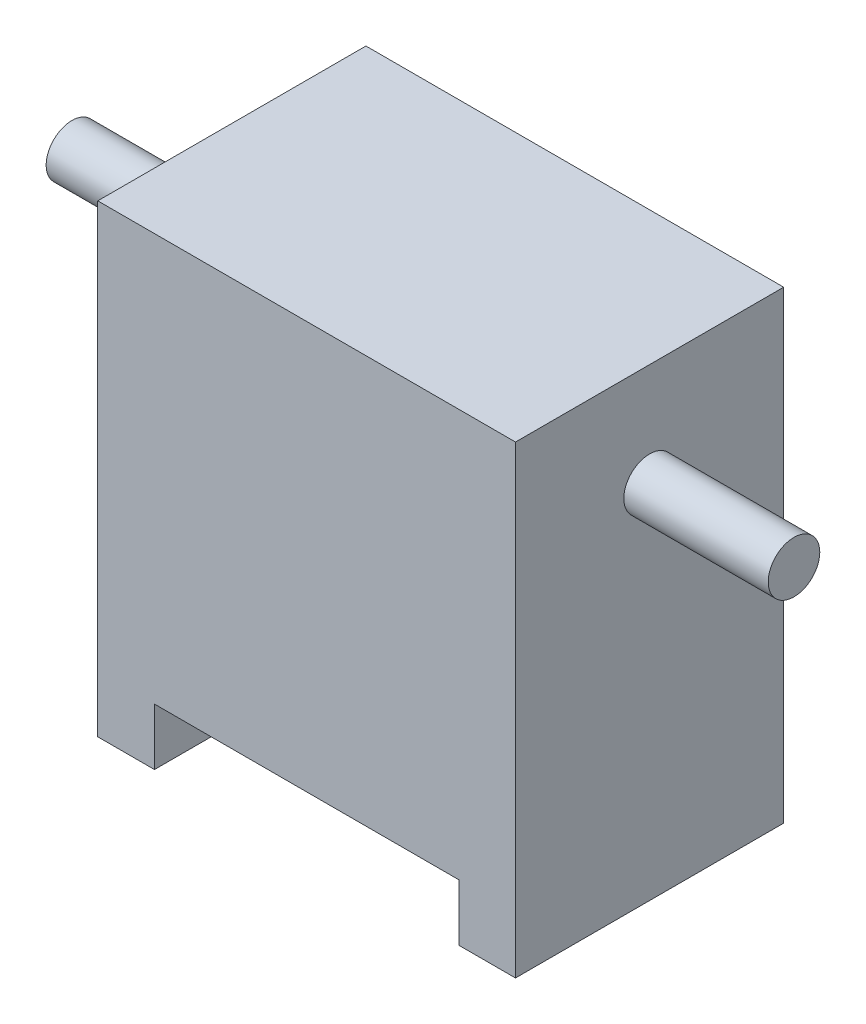
SolidWorks part; units mm, degrees
ref_plane "前视基准面" through (0, 0, 0) normal (0, 0, 1) x (1, 0, 0)
ref_plane "上视基准面" through (0, 0, 0) normal (0, 1, 0) x (1, 0, 0)
ref_plane "右视基准面" through (0, 0, 0) normal (1, 0, 0) x (0, 0, -1)
sketch "草图1" plane through (0, 0, 0) normal (0, 0, 1) x (1, 0, 0)
  line L0 (5.5, 38.1731) -> (5.5, -79.5851) construction
  line L1 (0, 0) -> (40.5, 0)
  line L2 (0, 0) -> (0, -45)
  line L3 (0, -45) -> (40.5, -45)
  line L4 (40.5, 0) -> (40.5, -45)
  line L5 (35, 38.1731) -> (35, -81.2046) construction
  line L6 (-37.7104, -39.5) -> (110.1236, -39.5) construction
  dimension "D1" = 40.5
  dimension "D2" = 45
  dimension "D3" = 5.5
  dimension "D4" = 5.5
  dimension "D5" = 5.5
extrude "凸台-拉伸1" add sketch "草图1" along normal blind 26
sketch "草图2" plane through (0, 0, 26) normal (0, 0, 1) x (1, 0, 0)
  line L0 (5.5, -39.5) -> (5.5, -45)
  line L1 (35, -39.5) -> (35, -45)
  line L2 (5.5, -39.5) -> (35, -39.5)
  line L3 (0, 0) -> (0, -45) construction
  line L4 (40.5, -45) -> (40.5, 0) construction
  line L5 (0, -45) -> (40.5, -45) construction
  line L6 (5.5, -45) -> (35, -45)
  dimension "D1" = 5.5
  dimension "D2" = 5.5
  dimension "D3" = 5.5
extrude "切除-拉伸1" cut sketch "草图2" against normal blind 38
sketch "草图3" plane through (40.5, 0, 0) normal (1, 0, 0) x (0, 0, -1)
  circle A0 centre (-13, -10) radius 2.5
extrude "凸台-拉伸2" add sketch "草图3" along normal blind 14 and the other way blind 56
